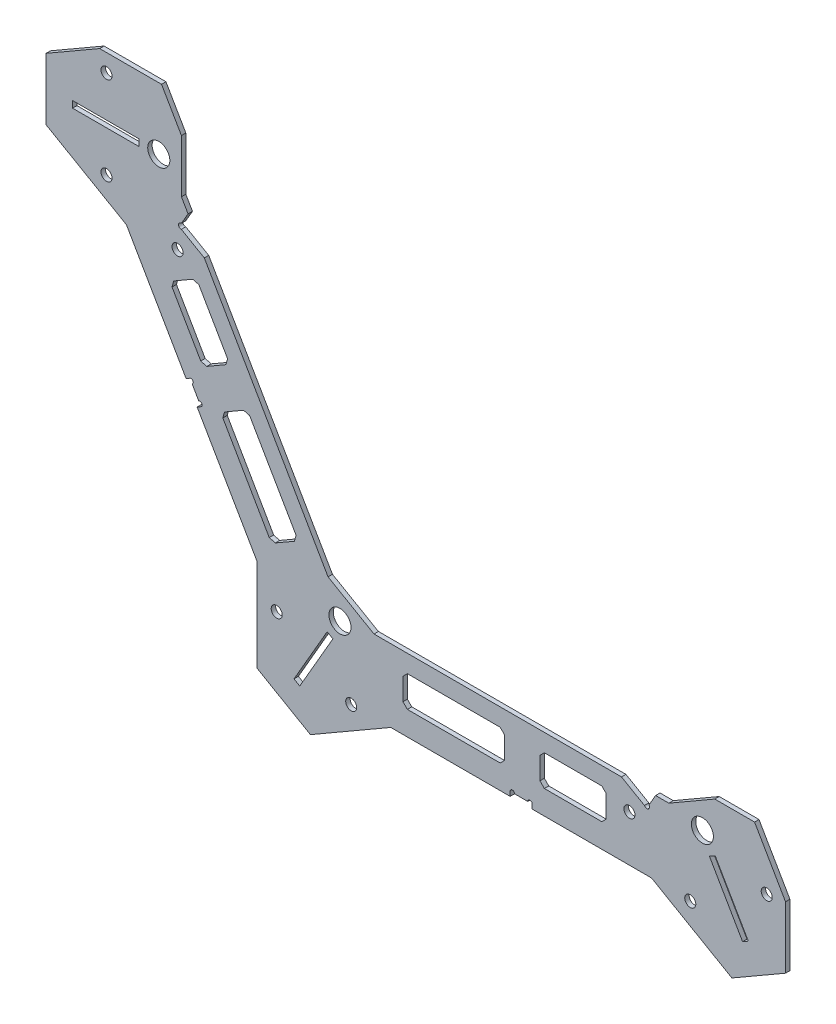
SolidWorks part; units mm, degrees
ref_plane "Alzado" through (0, 0, 0) normal (0, 0, 1) x (1, 0, 0)
ref_plane "Planta" through (0, 0, 0) normal (0, 1, 0) x (1, 0, 0)
ref_plane "Vista lateral" through (0, 0, 0) normal (1, 0, 0) x (0, 0, -1)
sketch "Croquis1" plane through (0, 0, 0) normal (0, 0, 1) x (1, 0, 0)
  line L0 (167.727, 514.3936) -> (861.0603, 514.3936) construction
  line L1 (61.2787, 23.8591) -> (67.3409, 20.3591)
  line L2 (67.3409, 20.3591) -> (85.5275, 30.8591)
  line L3 (85.5275, 30.8591) -> (112.5275, 30.8591)
  line L4 (112.5275, 30.8591) -> (112.5275, 31.8591)
  line L5 (113.5275, 31.8591) -> (116.5275, 31.8591)
  line L7 (117.5275, 30.8591) -> (144.5275, 30.8591)
  line L8 (144.5275, 30.8591) -> (162.714, 20.3591)
  line L9 (162.714, 20.3591) -> (174.8383, 27.3591)
  line L10 (174.8383, 27.3591) -> (174.8383, 41.3591)
  line L11 (174.8383, 41.3591) -> (167.8383, 53.4835)
  line L12 (167.8383, 53.4835) -> (158.8383, 53.4835)
  line L13 (158.8383, 53.4835) -> (148.446, 47.4835)
  line L14 (148.446, 47.4835) -> (145.446, 47.4835)
  line L15 (145.446, 47.4835) -> (143.946, 44.8854)
  line L17 (142.9211, 44.2729) -> (137.7249, 47.2729)
  line L18 (137.7249, 47.2729) -> (81.7249, 47.2729)
  line L19 (81.7249, 47.2729) -> (76.5287, 50.2729)
  line L20 (76.5287, 50.2729) -> (75.2787, 48.1078)
  line L21 (64.2787, 29.0552) -> (64.9283, 28.6802)
  line L22 (64.9283, 28.6802) -> (72.4283, 41.6706)
  line L23 (72.4283, 41.6706) -> (71.7787, 42.0456)
  line L36 (72.7787, 43.7777) -> (71.7787, 42.0456)
  line L37 (64.2787, 29.0552) -> (61.2787, 23.8591)
  line L46 (117.5275, 30.8591) -> (117.5275, 31.8591)
  line L47 (89.3864, 17.8778) -> (100.6236, 18.0431) construction
  line L48 (165.7762, 29.0552) -> (158.2762, 42.0456) construction
  line L49 (165.7762, 29.0552) -> (166.4257, 29.4302)
  line L50 (166.4257, 29.4302) -> (158.9257, 42.4206)
  line L51 (158.9257, 42.4206) -> (158.2762, 42.0456)
  line L52 (158.2762, 42.0456) -> (157.6266, 41.6706)
  line L53 (157.6266, 41.6706) -> (165.1266, 28.6802)
  line L54 (165.1266, 28.6802) -> (165.7762, 29.0552)
  line L55 (89.2775, 43.2729) -> (88.2775, 42.2729)
  line L56 (120.2775, 43.2729) -> (133.2775, 43.2729)
  line L57 (119.2775, 42.2729) -> (119.2775, 37.2729)
  line L58 (120.2775, 36.2729) -> (133.2775, 36.2729)
  line L59 (134.2775, 42.2729) -> (134.2775, 37.2729)
  line L60 (110.2775, 43.2729) -> (89.2775, 43.2729)
  line L61 (111.2775, 42.2729) -> (111.2775, 37.2729)
  line L62 (110.2775, 36.2729) -> (89.2775, 36.2729)
  line L63 (88.2775, 42.2729) -> (88.2775, 37.2729)
  line L64 (88.2775, 37.2729) -> (89.2775, 36.2729)
  line L65 (110.2775, 43.2729) -> (111.2775, 42.2729)
  line L66 (111.2775, 37.2729) -> (110.2775, 36.2729)
  line L67 (120.2775, 43.2729) -> (119.2775, 42.2729)
  line L68 (133.2775, 43.2729) -> (134.2775, 42.2729)
  line L69 (119.2775, 37.2729) -> (120.2775, 36.2729)
  line L70 (133.2775, 36.2729) -> (134.2775, 37.2729)
  circle A2 centre (76.5719, 30.8847) radius 1.25
  arc A3 (72.7787, 43.7777) -> (75.2787, 48.1078) centre (74.0287, 45.9427) ccw
  circle A4 centre (156.0262, 45.9427) radius 2.5
  arc A8 (112.5275, 31.8591) -> (113.5275, 31.8591) centre (113.0275, 31.8591) cw
  arc A12 (116.5275, 31.8591) -> (117.5275, 31.8591) centre (117.0275, 31.8591) cw
  arc A15 (142.9211, 44.2729) -> (143.946, 44.8854) centre (143.4641, 44.5279) ccw
  circle A16 centre (153.2868, 30.7094) radius 1.25
  circle A17 centre (170.5883, 40.6984) radius 1.25
  circle A18 centre (139.5275, 41.3247) radius 1.25
  point P50 (119.2775, 43.2729)
  point P51 (134.2775, 36.2729)
  point P52 (119.2775, 36.2729)
  point P53 (134.2775, 43.2729)
  point P54 (111.2775, 43.2729)
  point P55 (88.2775, 36.2729)
  point P58 (111.2775, 36.2729)
  point P59 (88.2775, 43.2729)
  dimension "D2" = 21
  dimension "D7" = 0.5
  dimension "D9" = 0.5
  dimension "D20" = 2.5
  dimension "D36" = 2.5
  dimension "D39" = 2.5
  dimension "D40" = 4.25
  dimension "D45" = 5
  dimension "D48" = 2.5
  dimension "D50" = 5
  dimension "D56" = 5.25
  dimension "D1" = 120
  dimension "D3" = 7
  dimension "D4" = 210
  dimension "D5" = 27
  dimension "D6" = 1
  dimension "D8" = 3
  dimension "D10" = 27
  dimension "D11" = 210
  dimension "D12" = 21
  dimension "D13" = 120
  dimension "D14" = 14
  dimension "D15" = 14
  dimension "D16" = 6
  dimension "D17" = 0.75
  dimension "D18" = 15
  dimension "D19" = 2
  dimension "D21" = 2.5
  dimension "D22" = 6
  dimension "D23" = 14
  dimension "D24" = 9
  dimension "D25" = 56
  dimension "D26" = 12
  dimension "D27" = 3
  dimension "D28" = 3
  dimension "D29" = 6
  dimension "D30" = 150
  dimension "D31" = 210
  dimension "D32" = 90
  dimension "D33" = 90
  dimension "D34" = 1
  dimension "D35" = 1
  dimension "D37" = 4.5
  dimension "D38" = 14
  dimension "D41" = 14
  dimension "D42" = 6
  dimension "D43" = 15
  dimension "D44" = 90
  dimension "D46" = 4.5
  dimension "D47" = 0
  dimension "D49" = 4.25
  dimension "D51" = 7
  dimension "D52" = 7
  dimension "D53" = 15
  dimension "D54" = 23
  dimension "D55" = 8
  dimension "D57" = 4
  dimension "D58" = 4
extrude "Saliente-Extruir1" add sketch "Croquis1" along normal blind 1
mirror "Simetría2" about plane through (35.6278, -20.5697, 1) normal (0.866, -0.5, 0) of "Saliente-Extruir1"
